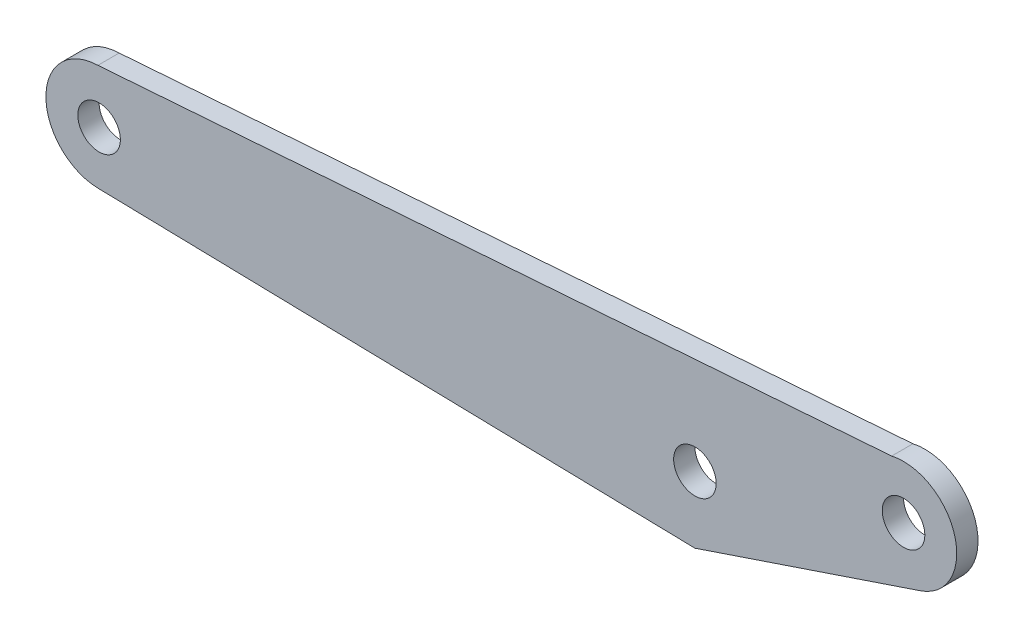
SolidWorks part; units mm, degrees
material "PLA"
ref_plane "Alzado" through (0, 0, 0) normal (0, 0, 1) x (1, 0, 0)
ref_plane "Planta" through (0, 0, 0) normal (0, 1, 0) x (1, 0, 0)
ref_plane "Vista lateral" through (0, 0, 0) normal (1, 0, 0) x (0, 0, -1)
sketch "Croquis1" plane through (0, 0, 0) normal (0, 0, 1) x (1, 0, 0)
  line L0 (-112, 0) -> (0, 0) construction
  line L1 (0, 0) -> (39.2195, 11.246) construction
  line L2 (-112.2229, 9.9975) -> (0, 12.5)
  line L3 (-112.2229, -9.9975) -> (0, -12.5)
  line L4 (0, 12.5) -> (36.9814, 20.9923)
  line L5 (0, -12.5) -> (42.4083, 1.7681)
  line L6 (0, 12.5) -> (0, -12.5) construction
  line L7 (-112.2229, 9.9975) -> (36.9814, 20.9923)
  arc A0 (-112.2229, 9.9975) -> (-112.2229, -9.9975) centre (-112, 0) ccw
  circle A1 centre (0, 0) radius 4
  arc A2 (42.4083, 1.7681) -> (36.9814, 20.9923) centre (39.2195, 11.246) ccw
  circle A3 centre (39.2195, 11.246) radius 4
  circle A4 centre (-112, 0) radius 4
  dimension "D4" = 8
  dimension "D5" = 20
  dimension "D6" = 8
  dimension "D7" = 20
  dimension "D8" = 8
  dimension "D1" = 16
  dimension "D2" = 40.8
  dimension "D3" = 112
  dimension "D9" = 25
extrude "Saliente-Extruir1" add sketch "Croquis1" along normal blind 4 contours L5 A2 L4 L2 A0 L3 A4 A3 A1 | L7 L2 L4
